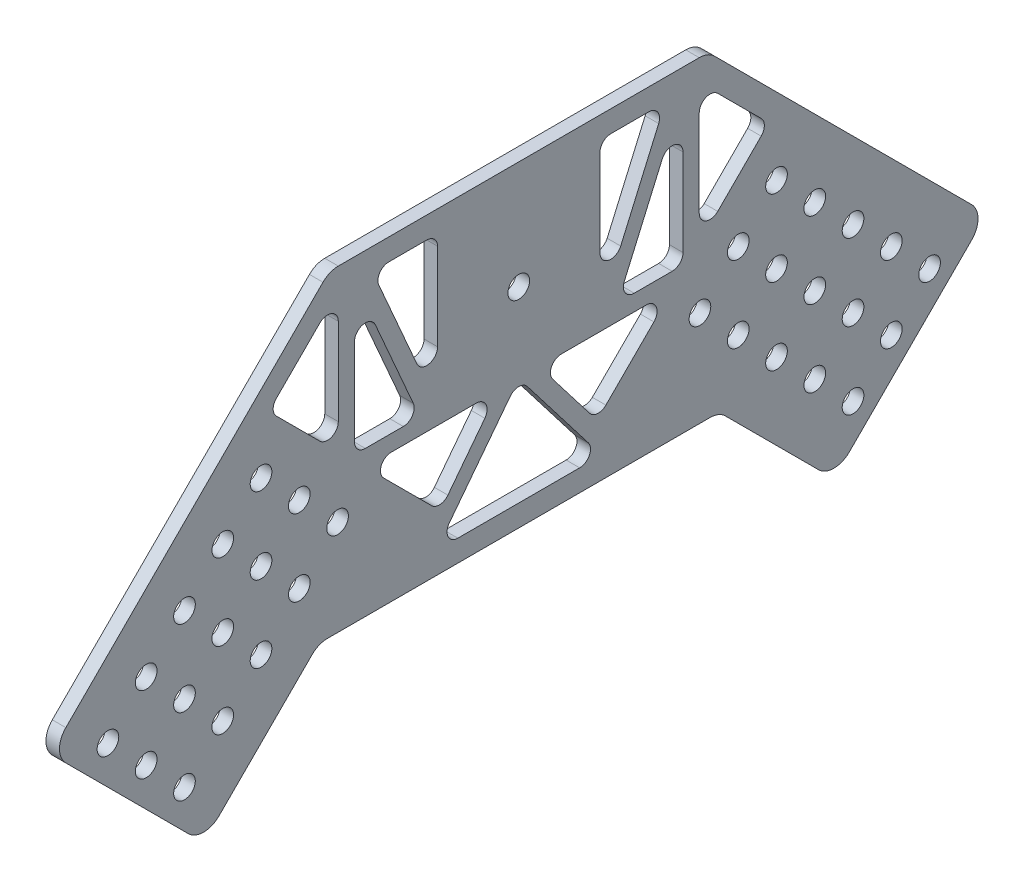
SolidWorks part; units mm, degrees
ref_plane "Front Plane" through (0, 0, 0) normal (0, 0, 1) x (1, 0, 0)
ref_plane "Top Plane" through (0, 0, 0) normal (0, 1, 0) x (1, 0, 0)
ref_plane "Right Plane" through (0, 0, 0) normal (1, 0, 0) x (0, 0, -1)
sketch "Sketch5" plane through (0, 0, 0) normal (1, 0, 0) x (0, 0, -1)
  line L0 (0, 50.8) -> (0, -76.2)
  line L1 (0, 0) -> (762, 0)
  line L2 (0, 0) -> (0, 50.8)
  line L3 (0, 50.8) -> (762, 50.8)
  line L4 (762, 0) -> (762, 50.8)
  line L5 (0, 50.8) -> (-82.55, 50.8)
  line L6 (-82.55, 50.8) -> (-82.55, -76.2)
  line L7 (-82.55, -76.2) -> (0, -76.2)
  line L8 (381, 0) -> (381, 192.0216) construction
  line L9 (762, 50.8) -> (762, -76.2)
  line L10 (844.55, 50.8) -> (844.55, -76.2)
  line L11 (762, 50.8) -> (844.55, 50.8)
  line L12 (844.55, -76.2) -> (762, -76.2)
  line L13 (-278.3903, -101.6) -> (1396.3209, -101.6) construction
  line L14 (82.55, 95.25) -> (381, 393.7)
  line L15 (917.6226, 157.1293) -> (1197.0226, 157.1293)
  line L16 (917.6226, 157.1293) -> (917.6226, -96.8707)
  line L17 (917.6226, -96.8707) -> (1197.0226, -96.8707)
  line L18 (1197.0226, 157.1293) -> (1197.0226, -96.8707)
  line L19 (0, 95.25) -> (762, 95.25)
  line L20 (0, 95.25) -> (0, 69.85)
  line L21 (0, 69.85) -> (762, 69.85)
  line L22 (762, 95.25) -> (762, 69.85)
  line L23 (381, 393.7) -> (679.45, 95.25)
  line L24 (381, 323.85) -> (791.5688, 122.6905)
  line L26 (802.1362, 159.2957) -> (1070.5742, 81.8014)
  line L27 (1070.5742, 81.8014) -> (1049.4394, 8.591)
  line L28 (1049.4394, 8.591) -> (781.0013, 86.0853)
  line L30 (781.0013, 86.0853) -> (802.1362, 159.2957)
  line L31 (-1447.8, 374.65) -> (-177.8, 374.65)
  line L32 (-177.8, 374.65) -> (-177.8, -101.6)
  line L33 (-1447.8, 374.65) -> (-1447.8, -101.6)
  line L34 (863.1448, 141.6834) -> (842.01, 68.473)
  line L35 (381, 323.85) -> (392.1755, 346.6594)
  line L36 (349.25, 361.95) -> (412.75, 361.95)
  line L37 (392.1755, 346.6594) -> (802.7443, 145.4999)
  line L38 (802.7443, 145.4999) -> (791.5688, 122.6905)
  line L39 (791.5688, 122.6905) -> (780.161, 99.9949)
  line L40 (780.161, 99.9949) -> (369.8245, 301.0406)
  line L41 (369.8245, 301.0406) -> (381, 323.85)
  circle A0 centre (50.8, -50.8) radius 50.8
  circle A1 centre (711.2, -50.8) radius 50.8
  circle A2 centre (381, 323.85) radius 12.7
  circle A3 centre (381, 323.85) radius 85.09
  point P38 (791.5688, 122.6905)
  dimension "D3" = 101.6
  dimension "D4" = 101.6
  dimension "D11" = 25.4
  dimension "D24" = 170.18
  dimension "D1" = 50.8
  dimension "D2" = 762
  dimension "D5" = 127
  dimension "D6" = 82.55
  dimension "D7" = 279.4
  dimension "D8" = 254
  dimension "D9" = 25.4
  dimension "D10" = 19.05
  dimension "D12" = 76.2
  dimension "D13" = 63.5
  dimension "D14" = 279.4
  dimension "D15" = 457.2
  dimension "D16" = 228.6
  dimension "D17" = 476.25
  dimension "D18" = 1270
  dimension "D19" = 558.8
  dimension "D20" = 80
  dimension "D21" = 63.5
  dimension "D22" = 45
  dimension "D23" = 38.1
  dimension "D25" = 25.4
  dimension "D26" = 25.4
sketch "Sketch6" plane through (0, 0, 0) normal (1, 0, 0) x (0, 0, -1)
  line L0 (762, 95.25) -> (762, 69.85) construction
  line L1 (0, 95.25) -> (762, 95.25) construction
  line L2 (0, 95.25) -> (0, 69.85) construction
  line L3 (0, 69.85) -> (762, 69.85) construction
  line L4 (762, 95.25) -> (762, 69.85)
  line L5 (0, 95.25) -> (762, 95.25)
  line L6 (0, 95.25) -> (0, 69.85)
  line L7 (0, 69.85) -> (762, 69.85)
  line L8 (349.25, 361.95) -> (412.75, 361.95) construction
  line L9 (381, 393.7) -> (679.45, 95.25) construction
  line L10 (82.55, 95.25) -> (381, 393.7) construction
  line L11 (349.25, 361.95) -> (412.75, 361.95)
  line L12 (381, 393.7) -> (679.45, 95.25)
  line L13 (82.55, 95.25) -> (381, 393.7)
  line L14 (317.5, 349.25) -> (317.5, 298.45)
  line L15 (317.5, 298.45) -> (838.2, 298.45)
  line L16 (838.2, 298.45) -> (838.2, 349.25)
  line L17 (838.2, 349.25) -> (317.5, 349.25)
  line L18 (154.392, 95.25) -> (344.892, 285.75)
  line L19 (344.892, 285.75) -> (417.108, 285.75)
  line L20 (417.108, 285.75) -> (607.608, 95.25)
  line L21 (381, -200000) -> (381, 200192.0216) construction
  line L22 (317.5, 69.85) -> (444.5, 69.85)
  line L23 (317.5, 69.85) -> (317.5, 171.45)
  line L24 (317.5, 171.45) -> (444.5, 171.45)
  line L25 (444.5, 69.85) -> (444.5, 171.45)
  circle A0 centre (381, 323.85) radius 12.7 construction
  circle A1 centre (381, 323.85) radius 12.7
  circle A2 centre (381, 323.85) radius 85.09 construction
  circle A3 centre (381, 323.85) radius 85.09
  text T0 "gearbox area"
  text T1 "sprocket"
  point P30 (381, 171.45)
  dimension "D1" = 50.8
  dimension "D2" = 25.4
  dimension "D3" = 520.7
  dimension "D4" = 63.5
  dimension "D5" = 50.8
  dimension "D6" = 50.8
  dimension "D7" = 76.2
  dimension "D8" = 101.6
  dimension "D9" = 127
sketch "tubes" plane through (0, 0, 0) normal (1, 0, 0) x (0, 0, -1)
  line L0 (158.8822, 99.7401) -> (122.9612, 135.6612)
  line L1 (0, 95.25) -> (762, 95.25)
  line L2 (0, 95.25) -> (0, 69.85)
  line L3 (0, 69.85) -> (762, 69.85)
  line L4 (762, 95.25) -> (762, 69.85)
  line L5 (158.8822, 99.7401) -> (351.9577, 292.8156)
  line L6 (351.9577, 292.8156) -> (316.0367, 328.7367)
  line L7 (316.0367, 328.7367) -> (122.9612, 135.6612)
  line L8 (82.55, 95.25) -> (381, 393.7) construction
  line L9 (154.392, 95.25) -> (344.892, 285.75) construction
  line L10 (158.8822, 99.7401) -> (154.392, 95.25) construction
  line L11 (381, -200000) -> (381, 200192.0216) construction
  line L12 (381, -200000) -> (381, 200192.0216) construction
  line L13 (603.1178, 99.7401) -> (410.0423, 292.8156)
  line L14 (410.0423, 292.8156) -> (445.9633, 328.7367)
  line L15 (445.9633, 328.7367) -> (639.0388, 135.6612)
  line L16 (603.1178, 99.7401) -> (639.0388, 135.6612)
  line L18 (12.7, 82.55) -> (25.4, 82.55) construction
  line L19 (158.8822, 117.7006) -> (167.8624, 108.7204) construction
  line L20 (158.8822, 117.7006) -> (149.9019, 108.7204) construction
  line L21 (158.8822, 117.7006) -> (149.9019, 126.6809) construction
  line L22 (158.8822, 117.7006) -> (167.8624, 126.6809) construction
  line L23 (603.1178, 117.7006) -> (594.1376, 126.6809) construction
  circle A0 centre (12.7, 82.55) radius 2.54
  circle A1 centre (25.4, 82.55) radius 2.54
  circle A2 centre (38.1, 82.55) radius 2.54
  circle A3 centre (50.8, 82.55) radius 2.54
  circle A4 centre (63.5, 82.55) radius 2.54
  circle A5 centre (76.2, 82.55) radius 2.54
  circle A6 centre (88.9, 82.55) radius 2.54
  circle A7 centre (101.6, 82.55) radius 2.54
  circle A8 centre (114.3, 82.55) radius 2.54
  circle A9 centre (127, 82.55) radius 2.54
  circle A10 centre (139.7, 82.55) radius 2.54
  circle A11 centre (152.4, 82.55) radius 2.54
  circle A12 centre (165.1, 82.55) radius 2.54
  circle A13 centre (177.8, 82.55) radius 2.54
  circle A14 centre (190.5, 82.55) radius 2.54
  circle A15 centre (203.2, 82.55) radius 2.54
  circle A16 centre (215.9, 82.55) radius 2.54
  circle A17 centre (228.6, 82.55) radius 2.54
  circle A18 centre (241.3, 82.55) radius 2.54
  circle A19 centre (254, 82.55) radius 2.54
  circle A20 centre (266.7, 82.55) radius 2.54
  circle A21 centre (279.4, 82.55) radius 2.54
  circle A22 centre (292.1, 82.55) radius 2.54
  circle A23 centre (304.8, 82.55) radius 2.54
  circle A24 centre (317.5, 82.55) radius 2.54
  circle A25 centre (330.2, 82.55) radius 2.54
  circle A26 centre (342.9, 82.55) radius 2.54
  circle A27 centre (355.6, 82.55) radius 2.54
  circle A28 centre (368.3, 82.55) radius 2.54
  circle A29 centre (381, 82.55) radius 2.54
  circle A30 centre (393.7, 82.55) radius 2.54
  circle A31 centre (406.4, 82.55) radius 2.54
  circle A32 centre (419.1, 82.55) radius 2.54
  circle A33 centre (431.8, 82.55) radius 2.54
  circle A34 centre (444.5, 82.55) radius 2.54
  circle A35 centre (457.2, 82.55) radius 2.54
  circle A36 centre (469.9, 82.55) radius 2.54
  circle A37 centre (482.6, 82.55) radius 2.54
  circle A38 centre (495.3, 82.55) radius 2.54
  circle A39 centre (508, 82.55) radius 2.54
  circle A40 centre (520.7, 82.55) radius 2.54
  circle A41 centre (533.4, 82.55) radius 2.54
  circle A42 centre (546.1, 82.55) radius 2.54
  circle A43 centre (558.8, 82.55) radius 2.54
  circle A44 centre (571.5, 82.55) radius 2.54
  circle A45 centre (584.2, 82.55) radius 2.54
  circle A46 centre (596.9, 82.55) radius 2.54
  circle A47 centre (609.6, 82.55) radius 2.54
  circle A48 centre (622.3, 82.55) radius 2.54
  circle A49 centre (635, 82.55) radius 2.54
  circle A50 centre (647.7, 82.55) radius 2.54
  circle A51 centre (660.4, 82.55) radius 2.54
  circle A52 centre (673.1, 82.55) radius 2.54
  circle A53 centre (685.8, 82.55) radius 2.54
  circle A54 centre (698.5, 82.55) radius 2.54
  circle A55 centre (711.2, 82.55) radius 2.54
  circle A56 centre (723.9, 82.55) radius 2.54
  circle A57 centre (736.6, 82.55) radius 2.54
  circle A58 centre (749.3, 82.55) radius 2.54
  circle A59 centre (762, 82.55) radius 2.54
  circle A60 centre (158.8822, 117.7006) radius 2.54
  circle A61 centre (149.9019, 126.6809) radius 2.54
  circle A62 centre (140.9217, 135.6612) radius 2.54
  circle A63 centre (167.8624, 126.6809) radius 2.54
  circle A64 centre (158.8822, 135.6612) radius 2.54
  circle A65 centre (149.9019, 144.6414) radius 2.54
  circle A66 centre (176.8427, 135.6612) radius 2.54
  circle A67 centre (167.8624, 144.6414) radius 2.54
  circle A68 centre (158.8822, 153.6217) radius 2.54
  circle A69 centre (185.8229, 144.6414) radius 2.54
  circle A70 centre (176.8427, 153.6217) radius 2.54
  circle A71 centre (167.8624, 162.6019) radius 2.54
  circle A72 centre (194.8032, 153.6217) radius 2.54
  circle A73 centre (185.8229, 162.6019) radius 2.54
  circle A74 centre (176.8427, 171.5822) radius 2.54
  circle A75 centre (203.7835, 162.6019) radius 2.54
  circle A76 centre (194.8032, 171.5822) radius 2.54
  circle A77 centre (185.8229, 180.5624) radius 2.54
  circle A78 centre (212.7637, 171.5822) radius 2.54
  circle A79 centre (203.7835, 180.5624) radius 2.54
  circle A80 centre (194.8032, 189.5427) radius 2.54
  circle A81 centre (221.744, 180.5624) radius 2.54
  circle A82 centre (212.7637, 189.5427) radius 2.54
  circle A83 centre (203.7835, 198.5229) radius 2.54
  circle A84 centre (230.7242, 189.5427) radius 2.54
  circle A85 centre (221.744, 198.5229) radius 2.54
  circle A86 centre (212.7637, 207.5032) radius 2.54
  circle A87 centre (239.7045, 198.5229) radius 2.54
  circle A88 centre (230.7242, 207.5032) radius 2.54
  circle A89 centre (221.744, 216.4835) radius 2.54
  circle A90 centre (248.6847, 207.5032) radius 2.54
  circle A91 centre (239.7045, 216.4835) radius 2.54
  circle A92 centre (230.7242, 225.4637) radius 2.54
  circle A93 centre (257.665, 216.4835) radius 2.54
  circle A94 centre (248.6847, 225.4637) radius 2.54
  circle A95 centre (239.7045, 234.444) radius 2.54
  circle A96 centre (266.6453, 225.4637) radius 2.54
  circle A97 centre (257.665, 234.444) radius 2.54
  circle A98 centre (248.6847, 243.4242) radius 2.54
  circle A99 centre (275.6255, 234.444) radius 2.54
  circle A100 centre (266.6453, 243.4242) radius 2.54
  circle A101 centre (257.665, 252.4045) radius 2.54
  circle A102 centre (284.6058, 243.4242) radius 2.54
  circle A103 centre (275.6255, 252.4045) radius 2.54
  circle A104 centre (266.6453, 261.3847) radius 2.54
  circle A105 centre (293.586, 252.4045) radius 2.54
  circle A106 centre (284.6058, 261.3847) radius 2.54
  circle A107 centre (275.6255, 270.365) radius 2.54
  circle A108 centre (302.5663, 261.3847) radius 2.54
  circle A109 centre (293.586, 270.365) radius 2.54
  circle A110 centre (284.6058, 279.3453) radius 2.54
  circle A111 centre (311.5465, 270.365) radius 2.54
  circle A112 centre (302.5663, 279.3453) radius 2.54
  circle A113 centre (293.586, 288.3255) radius 2.54
  circle A114 centre (320.5268, 279.3453) radius 2.54
  circle A115 centre (311.5465, 288.3255) radius 2.54
  circle A116 centre (302.5663, 297.3058) radius 2.54
  circle A117 centre (329.507, 288.3255) radius 2.54
  circle A118 centre (320.5268, 297.3058) radius 2.54
  circle A119 centre (311.5465, 306.286) radius 2.54
  circle A120 centre (338.4873, 297.3058) radius 2.54
  circle A121 centre (329.507, 306.286) radius 2.54
  circle A122 centre (320.5268, 315.2663) radius 2.54
  circle A123 centre (621.0783, 135.6612) radius 2.54
  circle A124 centre (612.0981, 126.6809) radius 2.54
  circle A125 centre (603.1178, 117.7006) radius 2.54
  circle A126 centre (594.1376, 126.6809) radius 2.54
  circle A127 centre (603.1178, 135.6612) radius 2.54
  circle A128 centre (612.0981, 144.6414) radius 2.54
  circle A129 centre (585.1573, 135.6612) radius 2.54
  circle A130 centre (594.1376, 144.6414) radius 2.54
  circle A131 centre (603.1178, 153.6217) radius 2.54
  circle A132 centre (576.1771, 144.6414) radius 2.54
  circle A133 centre (585.1573, 153.6217) radius 2.54
  circle A134 centre (594.1376, 162.6019) radius 2.54
  circle A135 centre (567.1968, 153.6217) radius 2.54
  circle A136 centre (576.1771, 162.6019) radius 2.54
  circle A137 centre (585.1573, 171.5822) radius 2.54
  circle A138 centre (558.2165, 162.6019) radius 2.54
  circle A139 centre (567.1968, 171.5822) radius 2.54
  circle A140 centre (576.1771, 180.5624) radius 2.54
  circle A141 centre (549.2363, 171.5822) radius 2.54
  circle A142 centre (558.2165, 180.5624) radius 2.54
  circle A143 centre (567.1968, 189.5427) radius 2.54
  circle A144 centre (540.256, 180.5624) radius 2.54
  circle A145 centre (549.2363, 189.5427) radius 2.54
  circle A146 centre (558.2165, 198.5229) radius 2.54
  circle A147 centre (531.2758, 189.5427) radius 2.54
  circle A148 centre (540.256, 198.5229) radius 2.54
  circle A149 centre (549.2363, 207.5032) radius 2.54
  circle A150 centre (522.2955, 198.5229) radius 2.54
  circle A151 centre (531.2758, 207.5032) radius 2.54
  circle A152 centre (540.256, 216.4835) radius 2.54
  circle A153 centre (513.3153, 207.5032) radius 2.54
  circle A154 centre (522.2955, 216.4835) radius 2.54
  circle A155 centre (531.2758, 225.4637) radius 2.54
  circle A156 centre (504.335, 216.4835) radius 2.54
  circle A157 centre (513.3153, 225.4637) radius 2.54
  circle A158 centre (522.2955, 234.444) radius 2.54
  circle A159 centre (495.3547, 225.4637) radius 2.54
  circle A160 centre (504.335, 234.444) radius 2.54
  circle A161 centre (513.3153, 243.4242) radius 2.54
  circle A162 centre (486.3745, 234.444) radius 2.54
  circle A163 centre (495.3547, 243.4242) radius 2.54
  circle A164 centre (504.335, 252.4045) radius 2.54
  circle A165 centre (477.3942, 243.4242) radius 2.54
  circle A166 centre (486.3745, 252.4045) radius 2.54
  circle A167 centre (495.3547, 261.3847) radius 2.54
  circle A168 centre (468.414, 252.4045) radius 2.54
  circle A169 centre (477.3942, 261.3847) radius 2.54
  circle A170 centre (486.3745, 270.365) radius 2.54
  circle A171 centre (459.4337, 261.3847) radius 2.54
  circle A172 centre (468.414, 270.365) radius 2.54
  circle A173 centre (477.3942, 279.3453) radius 2.54
  circle A174 centre (450.4535, 270.365) radius 2.54
  circle A175 centre (459.4337, 279.3453) radius 2.54
  circle A176 centre (468.414, 288.3255) radius 2.54
  circle A177 centre (441.4732, 279.3453) radius 2.54
  circle A178 centre (450.4535, 288.3255) radius 2.54
  circle A179 centre (459.4337, 297.3058) radius 2.54
  circle A180 centre (432.493, 288.3255) radius 2.54
  circle A181 centre (441.4732, 297.3058) radius 2.54
  circle A182 centre (450.4535, 306.286) radius 2.54
  circle A183 centre (423.5127, 297.3058) radius 2.54
  circle A184 centre (432.493, 306.286) radius 2.54
  circle A185 centre (441.4732, 315.2663) radius 2.54
  circle A186 centre (381, 323.85) radius 12.7 construction
  circle A187 centre (381, 323.85) radius 12.7
  dimension "D5" = 5.08
  dimension "D10" = 5.08
  dimension "D1" = 273.05
  dimension "D2" = 6.35
  dimension "D3" = 12.7
  dimension "D4" = 12.7
  dimension "D7" = 12.7
  dimension "D8" = 12.7
  dimension "D9" = 12.7
  dimension "D12" = 12.7
  dimension "D14" = 12.7
  dimension "D16" = 12.7
  dimension "D6" = 60
  dimension "D11" = 3
  dimension "D13" = 21
  dimension "D15" = 21
sketch "Sketch7" plane through (0, 0, 0) normal (1, 0, 0) x (0, 0, -1)
  line L0 (307.0564, 247.9144) -> (333.9972, 274.8551)
  line L2 (428.0028, 274.8551) -> (454.9436, 247.9144)
  line L3 (454.9436, 247.9144) -> (490.8646, 283.8354)
  line L4 (490.8646, 283.8354) -> (425.45, 349.25)
  line L6 (336.55, 349.25) -> (271.1354, 283.8354)
  line L7 (271.1354, 283.8354) -> (307.0564, 247.9144)
  line L8 (154.392, 95.25) -> (344.892, 285.75) construction
  line L9 (82.55, 95.25) -> (381, 393.7) construction
  line L10 (417.108, 285.75) -> (607.608, 95.25) construction
  line L11 (275.6255, 270.365) -> (284.6058, 279.3453) construction
  line L12 (477.3942, 279.3453) -> (486.3745, 270.365) construction
  line L13 (333.9972, 274.8551) -> (428.0028, 274.8551)
  line L14 (333.9972, 274.8551) -> (280.1156, 274.8551) construction
  line L15 (381, 393.7) -> (679.45, 95.25) construction
  line L16 (336.55, 349.25) -> (425.45, 349.25)
  line L17 (838.2, 349.25) -> (317.5, 349.25) construction
  line L18 (284.6058, 279.3453) -> (293.586, 288.3255) construction
  line L19 (284.6058, 279.3453) -> (293.586, 270.365) construction
  line L20 (477.3942, 279.3453) -> (468.414, 288.3255) construction
  line L21 (477.3942, 279.3453) -> (468.414, 270.365) construction
  line L22 (333.9972, 274.8551) -> (351.9577, 292.8156) construction
  line L23 (351.9577, 292.8156) -> (316.0367, 328.7367) construction
  line L24 (428.0028, 274.8551) -> (410.0423, 292.8156) construction
  line L25 (410.0423, 292.8156) -> (445.9633, 328.7367) construction
  line L26 (322.3228, 327.8386) -> (338.6542, 344.17)
  line L27 (338.6542, 344.17) -> (338.6542, 311.5073)
  line L28 (338.6542, 311.5073) -> (322.3228, 327.8386)
  line L29 (381, 349.25) -> (381, 274.8551) construction
  line L30 (342.4642, 344.17) -> (342.4642, 309.0234)
  line L31 (342.4642, 309.0234) -> (357.7934, 309.0234)
  line L32 (357.7934, 309.0234) -> (342.4642, 344.17)
  line L33 (346.6208, 344.17) -> (361.95, 344.17)
  line L35 (361.95, 309.0234) -> (346.6208, 344.17)
  line L36 (344.9481, 305.2134) -> (362.6063, 287.5551)
  line L37 (362.6063, 287.5551) -> (376.1928, 305.2134)
  line L38 (376.1928, 305.2134) -> (344.9481, 305.2134)
  line L39 (400.4493, 279.9351) -> (361.5507, 279.9351)
  line L40 (361.5507, 279.9351) -> (381, 305.2134)
  line L41 (338.6542, 311.5073) -> (344.9481, 305.2134) construction
  line L42 (338.6542, 344.17) -> (346.6208, 344.17) construction
  line L43 (357.7934, 309.0234) -> (361.95, 309.0234) construction
  line L44 (376.1928, 305.2134) -> (385.8072, 305.2134) construction
  line L45 (361.95, 309.0234) -> (361.95, 344.17)
  line L46 (404.2066, 309.0234) -> (400.05, 309.0234) construction
  line L47 (423.3458, 344.17) -> (415.3792, 344.17) construction
  line L48 (423.3458, 311.5073) -> (417.0519, 305.2134) construction
  line L49 (400.05, 309.0234) -> (400.05, 344.17)
  line L50 (400.4493, 279.9351) -> (381, 305.2134)
  line L51 (385.8072, 305.2134) -> (417.0519, 305.2134)
  line L52 (399.3937, 287.5551) -> (385.8072, 305.2134)
  line L53 (417.0519, 305.2134) -> (399.3937, 287.5551)
  line L54 (400.05, 309.0234) -> (415.3792, 344.17)
  line L55 (415.3792, 344.17) -> (400.05, 344.17)
  line L56 (404.2066, 309.0234) -> (419.5358, 344.17)
  line L57 (419.5358, 309.0234) -> (404.2066, 309.0234)
  line L58 (419.5358, 344.17) -> (419.5358, 309.0234)
  line L59 (423.3458, 311.5073) -> (439.6772, 327.8386)
  line L60 (423.3458, 344.17) -> (423.3458, 311.5073)
  line L61 (439.6772, 327.8386) -> (423.3458, 344.17)
  circle A0 centre (284.6058, 279.3453) radius 2.54
  circle A1 centre (293.586, 288.3255) radius 2.54
  circle A2 centre (302.5663, 297.3058) radius 2.54
  circle A3 centre (311.5465, 306.286) radius 2.54
  circle A4 centre (320.5268, 315.2663) radius 2.54
  circle A5 centre (302.5663, 279.3453) radius 2.54
  circle A6 centre (311.5465, 288.3255) radius 2.54
  circle A7 centre (320.5268, 297.3058) radius 2.54
  circle A8 centre (329.507, 306.286) radius 2.54
  circle A9 centre (311.5465, 270.365) radius 2.54
  circle A10 centre (320.5268, 279.3453) radius 2.54
  circle A11 centre (329.507, 288.3255) radius 2.54
  circle A12 centre (338.4873, 297.3058) radius 2.54
  circle A13 centre (293.586, 270.365) radius 2.54
  circle A14 centre (302.5663, 261.3847) radius 2.54
  circle A15 centre (477.3942, 279.3453) radius 2.54
  circle A16 centre (468.414, 288.3255) radius 2.54
  circle A17 centre (459.4337, 297.3058) radius 2.54
  circle A18 centre (450.4535, 306.286) radius 2.54
  circle A19 centre (441.4732, 315.2663) radius 2.54
  circle A20 centre (459.4337, 279.3453) radius 2.54
  circle A21 centre (450.4535, 288.3255) radius 2.54
  circle A22 centre (441.4732, 297.3058) radius 2.54
  circle A23 centre (432.493, 306.286) radius 2.54
  circle A24 centre (450.4535, 270.365) radius 2.54
  circle A25 centre (441.4732, 279.3453) radius 2.54
  circle A26 centre (432.493, 288.3255) radius 2.54
  circle A27 centre (423.5127, 297.3058) radius 2.54
  circle A28 centre (468.414, 270.365) radius 2.54
  circle A29 centre (459.4337, 261.3847) radius 2.54
  circle A30 centre (381, 323.85) radius 2.54
  point P22 (280.1156, 274.8551)
  point P27 (481.8844, 274.8551)
  point P129 (381, 279.9351)
  dimension "D1" = 5.08
  dimension "D6" = 5.08
  dimension "D11" = 5.08
  dimension "D4" = 12.7
  dimension "D5" = 12.7
  dimension "D9" = 12.7
  dimension "D10" = 12.7
  dimension "D12" = 63.5
  dimension "D13" = 63.5
  dimension "D14" = 5.08
  dimension "D15" = 5.08
  dimension "D16" = 3.81
  dimension "D17" = 3.81
  dimension "D18" = 5.08
  dimension "D19" = 3.81
  dimension "D20" = 3.81
  dimension "D21" = 3.81
  dimension "D22" = 3.81
  dimension "D23" = 19.05
  dimension "D25" = 34.1683
  dimension "D26" = 12.7
  dimension "D2" = 5
  dimension "D3" = 3
  dimension "D7" = 5
  dimension "D8" = 3
extrude "Boss-Extrude1" add sketch "Sketch7" along normal blind 3.175 contours A28 L4 L16 L6 L7 L0 L13 L2 L3 A30 A15 A14 A13 A0 L61 L59 L60 L55 L54 L49 L50 L39 L40 L45 L35 L33 L38 L37 L36 L32 L31 L30 L27 L28 L26 L51 L53
fillet "Fillet1" radius 2.54 27 edges at (1.5875, 311.5073, -423.3458) (1.5875, 327.8386, -439.6772) (1.5875, 344.17, -423.3458) (1.5875, 344.17, -400.05) (1.5875, 309.0234, -400.05) (1.5875, 344.17, -415.3792) (1.5875, 309.0234, -404.2066) (1.5875, 309.0234, -419.5358) (1.5875, 279.9351, -361.5507) (1.5875, 279.9351, -400.4493) (1.5875, 305.2134, -381) (1.5875, 287.5551, -362.6063) (1.5875, 305.2134, -376.1928) (1.5875, 305.2134, -344.9481) (1.5875, 305.2134, -417.0519) (1.5875, 305.2134, -385.8072) (1.5875, 287.5551, -399.3937) (1.5875, 309.0234, -342.4642) (1.5875, 309.0234, -357.7934) (1.5875, 344.17, -342.4642) (1.5875, 344.17, -361.95) (1.5875, 344.17, -346.6208) (1.5875, 309.0234, -361.95) (1.5875, 344.17, -338.6542) (1.5875, 327.8386, -322.3228) (1.5875, 311.5073, -338.6542) (1.5875, 344.17, -419.5358)
fillet "Fillet2" radius 5.08 8 edges at (1.5875, 283.8354, -271.1354) (1.5875, 349.25, -425.45) (1.5875, 283.8354, -490.8646) (1.5875, 247.9144, -454.9436) (1.5875, 274.8551, -428.0028) (1.5875, 274.8551, -333.9972) (1.5875, 247.9144, -307.0564) (1.5875, 349.25, -336.55)
